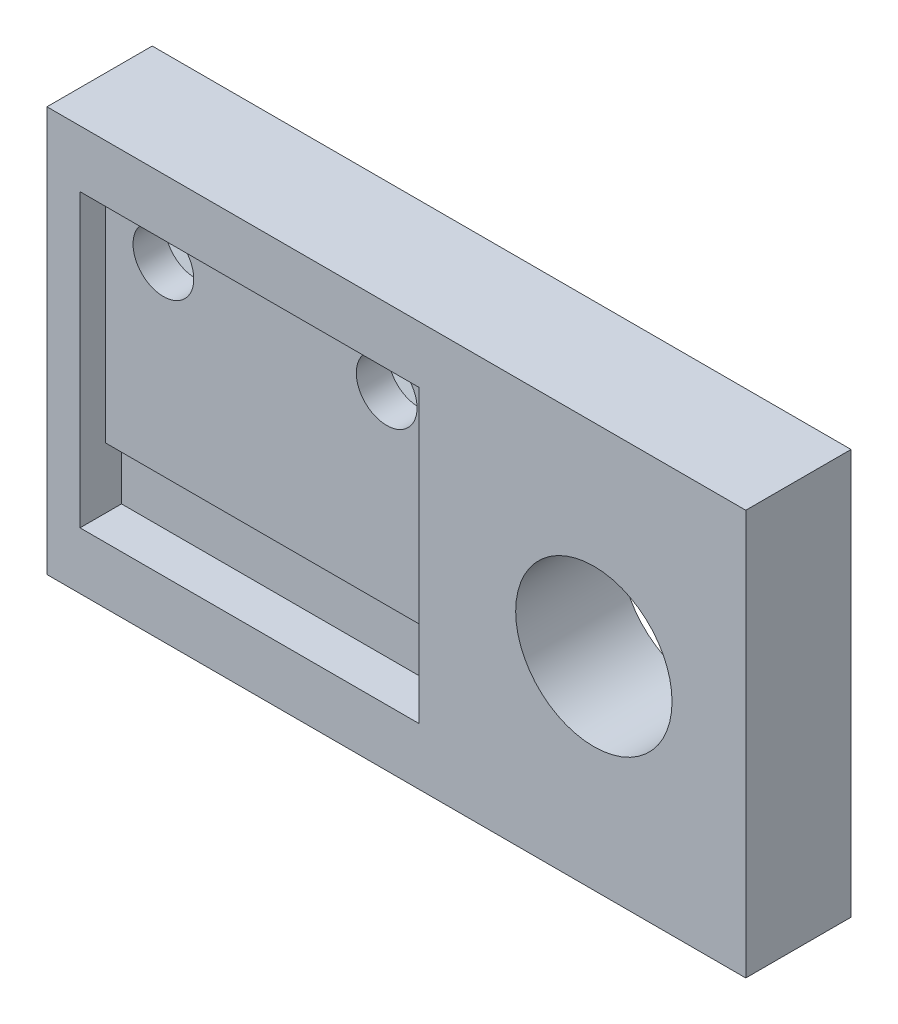
SolidWorks part; units mm, degrees
ref_plane "Front Plane" through (0, 0, 0) normal (0, 0, 1) x (1, 0, 0)
ref_plane "Top Plane" through (0, 0, 0) normal (0, 1, 0) x (1, 0, 0)
ref_plane "Right Plane" through (0, 0, 0) normal (1, 0, 0) x (0, 0, -1)
sketch "Sketch1" plane through (0, 0, 0) normal (0, 0, 1) x (1, 0, 0)
  line L0 (19.7, 12.7) -> (34.29, 12.7) construction
  line L1 (0, 0) -> (43.815, 0)
  line L2 (0, 0) -> (0, 25.4)
  line L3 (0, 25.4) -> (43.815, 25.4)
  line L4 (43.815, 0) -> (43.815, 25.4)
  line L5 (5.7, 19.05) -> (19.7, 19.05) construction
  line L6 (5.7, 19.05) -> (5.7, 6.35) construction
  line L7 (5.7, 6.35) -> (19.7, 6.35) construction
  line L8 (19.7, 19.05) -> (19.7, 6.35) construction
  line L9 (12.7, 19.05) -> (12.7, 25.4) construction
  line L10 (12.7, 6.35) -> (12.7, 0) construction
  line L11 (1.27, 24.13) -> (1.27, 25.4) construction
  line L12 (24.13, 1.27) -> (1.27, 1.27) construction
  line L13 (24.13, 1.27) -> (24.13, 24.13) construction
  line L14 (24.13, 24.13) -> (1.27, 24.13) construction
  line L15 (1.27, 1.27) -> (1.27, 24.13) construction
  line L16 (24.13, 1.27) -> (1.27, 24.13) construction
  line L17 (24.13, 24.13) -> (1.27, 1.27) construction
  line L18 (1.27, 24.13) -> (0, 24.13) construction
  circle A0 centre (5.7, 19.05) radius 1.904
  circle A1 centre (19.7, 19.05) radius 1.904
  circle A2 centre (19.7, 6.35) radius 1.904 construction
  circle A3 centre (5.7, 6.35) radius 1.904 construction
  circle A4 centre (34.29, 12.7) radius 4.9022
  point P20 (12.7, 12.7)
  dimension "D1" = 9.8044
  dimension "D2" = 3.808
  dimension "D3" = 12.7
  dimension "D4" = 14
  dimension "D5" = 25.4
  dimension "D6" = 22.86
  dimension "D7" = 1.27
  dimension "D8" = 43.815
  dimension "D9" = 9.525
extrude "Boss-Extrude1" add sketch "Sketch1" along normal blind 2
sketch "Sketch2" plane through (0, 0, 2) normal (0, 0, 1) x (1, 0, 0)
  line L0 (5.7, 19.05) -> (19.7, 19.05) construction
  line L1 (12.7, 19.05) -> (12.7, 12.7) construction
  line L3 (2.073, 3.573) -> (23.327, 3.573)
  line L4 (0, 25.4) -> (0, 0)
  line L5 (0, 0) -> (43.815, 0)
  line L6 (43.815, 0) -> (43.815, 25.4)
  line L7 (43.815, 25.4) -> (0, 25.4)
  line L8 (0, 25.4) -> (0, 0)
  line L9 (0, 0) -> (43.815, 0)
  line L10 (43.815, 0) -> (43.815, 25.4)
  line L11 (43.815, 25.4) -> (0, 25.4)
  line L12 (2.073, 3.573) -> (2.073, 21.827)
  line L13 (2.073, 21.827) -> (23.327, 21.827)
  line L14 (23.327, 3.573) -> (23.327, 21.827)
  line L15 (2.073, 3.573) -> (23.327, 21.827) construction
  line L16 (2.073, 21.827) -> (23.327, 3.573) construction
  circle A0 centre (34.29, 12.7) radius 4.9022 construction
  circle A1 centre (34.29, 12.7) radius 4.9022
  point P12 (12.7, 12.7)
  point P13 (12.7, 12.7)
  point P23 (0, 0)
  dimension "D2" = 21.254
  dimension "D3" = 18.254
  dimension "D1" = 0
extrude "Boss-Extrude2" add sketch "Sketch2" along normal blind 1.6
sketch "Sketch3" plane through (0, 0, 0) normal (0, 0, -1) x (-1, 0, 0)
  line L1 (-16.569, 17.2423) -> (-16.569, 20.8577)
  line L2 (-16.569, 20.8577) -> (-19.7, 22.6654)
  line L3 (-19.7, 22.6654) -> (-22.831, 20.8577)
  line L4 (0, 0) -> (0, 25.4)
  line L5 (0, 25.4) -> (-43.815, 25.4)
  line L6 (-43.815, 25.4) -> (-43.815, 0)
  line L7 (-43.815, 0) -> (0, 0)
  line L8 (0, 0) -> (0, 25.4)
  line L9 (0, 25.4) -> (-43.815, 25.4)
  line L10 (-43.815, 25.4) -> (-43.815, 0)
  line L11 (-43.815, 0) -> (0, 0)
  line L12 (-22.831, 20.8577) -> (-22.831, 17.2423)
  line L13 (-22.831, 17.2423) -> (-19.7, 15.4346)
  line L14 (-19.7, 15.4346) -> (-16.569, 17.2423)
  line L15 (-2.569, 20.8577) -> (-5.7, 22.6654)
  line L16 (-5.7, 22.6654) -> (-8.831, 20.8577)
  line L17 (-8.831, 20.8577) -> (-8.831, 17.2423)
  line L18 (-8.831, 17.2423) -> (-5.7, 15.4346)
  line L19 (-5.7, 15.4346) -> (-2.569, 17.2423)
  line L20 (-2.569, 17.2423) -> (-2.569, 20.8577)
  circle A0 centre (-34.29, 12.7) radius 4.9022 construction
  circle A1 centre (-34.29, 12.7) radius 4.9022
  circle A2 centre (-19.7, 19.05) radius 3.131 construction
  circle A3 centre (-5.7, 19.05) radius 3.131 construction
  circle A6 centre (-5.7, 19.05) radius 1.904 construction
  dimension "D2" = 6.262
  dimension "D1" = 0
extrude "Boss-Extrude3" add sketch "Sketch3" along normal blind 3
sketch "Sketch5" plane through (0, 0, 2) normal (0, 0, 1) x (1, 0, 0)
  line L0 (2.073, 21.827) -> (2.073, 3.573) construction
  line L1 (2.073, 7.383) -> (23.327, 7.383)
  line L2 (2.073, 7.383) -> (2.073, 3.573)
  line L3 (2.073, 3.573) -> (23.327, 3.573)
  line L4 (23.327, 7.383) -> (23.327, 3.573)
  dimension "D1" = 3.81
extrude "Cut-Extrude1" cut sketch "Sketch5" against normal blind 1
